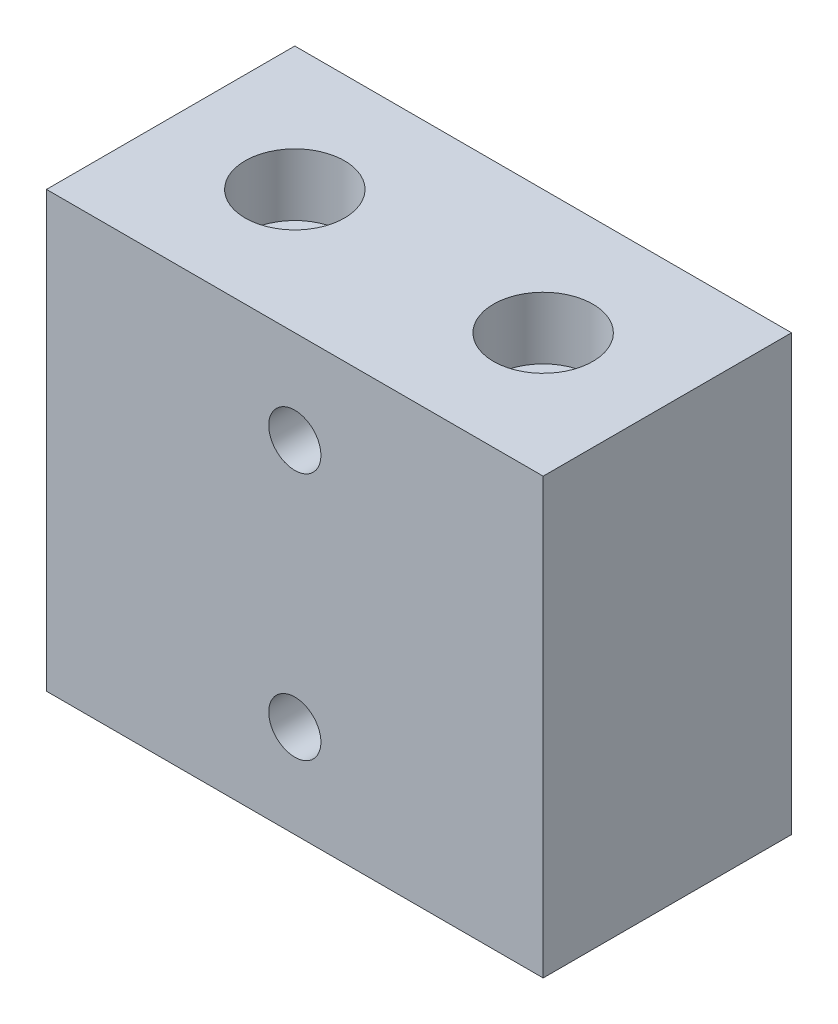
SolidWorks part; units mm, degrees
ref_plane "Front Plane" through (0, 0, 0) normal (0, 0, 1) x (1, 0, 0)
ref_plane "Top Plane" through (0, 0, 0) normal (0, 1, 0) x (1, 0, 0)
ref_plane "Right Plane" through (0, 0, 0) normal (1, 0, 0) x (0, 0, -1)
sketch "Sketch1" plane through (0, 0, 0) normal (0, 1, 0) x (1, 0, 0)
  line L0 (10, 0) -> (-10, 0) construction
  line L2 (-20, 10) -> (20, 10)
  line L3 (-20, 10) -> (-20, -10)
  line L4 (-20, -10) -> (20, -10)
  line L5 (20, 10) -> (20, -10)
  line L6 (-20, 10) -> (20, -10) construction
  line L7 (-20, -10) -> (20, 10) construction
  circle A0 centre (-10, 0) radius 2.5
  circle A1 centre (10, 0) radius 2.5
  point P4 (0, 0)
  point P7 (0, 0)
  point P12 (-111.8009, -2.0276)
  dimension "D1" = 5
  dimension "D2" = 5
  dimension "D3" = 20
  dimension "D4" = 20
  dimension "D5" = 40
extrude "Boss-Extrude1" add sketch "Sketch1" along normal blind 35
sketch "Sketch2" plane through (0, 35, 0) normal (0, 1, 0) x (1, 0, 0)
  circle A0 centre (-10, 0) radius 4
  circle A1 centre (10, 0) radius 4
  dimension "D1" = 8
  dimension "D2" = 8
extrude "Cut-Extrude1" cut sketch "Sketch2" against normal blind 5
sketch "Sketch3" plane through (0, 0, 10) normal (0, 0, 1) x (1, 0, 0)
  line L0 (0, 0) -> (0, 35) construction
  line L1 (-20, 35) -> (20, 35) construction
  circle A0 centre (0, 27.5) radius 2.1
  circle A1 centre (0, 7.5) radius 2.1
  point P9 (0, 28.4941)
  dimension "D1" = 4.2
  dimension "D2" = 4.2
  dimension "D3" = 20
  dimension "D4" = 7.5
extrude "Cut-Extrude2" cut sketch "Sketch3" against normal through all
